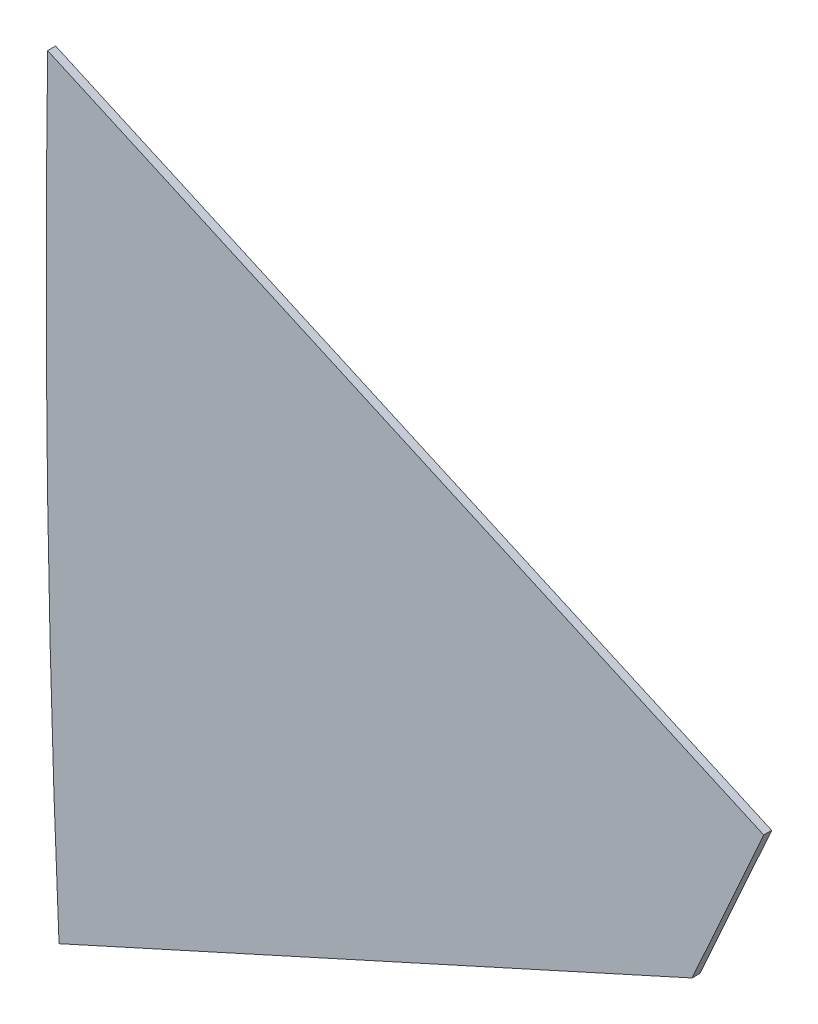
SolidWorks part; units mm, degrees
ref_plane "Plane Left" through (0, 0, 0) normal (0, 0, 1) x (1, 0, 0)
ref_plane "Plane Top" through (0, 0, 0) normal (0, 1, 0) x (1, 0, 0)
ref_plane "Plane Front" through (0, 0, 0) normal (1, 0, 0) x (0, 0, -1)
sketch "Sketch, Layout in Left plane" plane through (0, 0, 0) normal (0, 0, 1) x (1, 0, 0)
  line L0 (0, 0) -> (2438.4, 0) construction
  line L1 (2438.4, 0) -> (3438.525, 5791.2) construction
  line L2 (2438.4, 0) -> (3591.5584, 144.7101) construction
  line L4 (9.525, -304.8) -> (3438.525, 5791.2)
  line L5 (2438.4, 0) -> (2119.6797, -1845.5425) construction
  line L6 (2438.4, 0) -> (1532.9859, -517.7594) construction
  line L7 (1532.9859, -517.7594) -> (3591.5584, 144.7101) construction
  line L8 (1532.9859, -517.7594) -> (2119.6797, -1845.5425) construction
  line L9 (1532.9859, -517.7594) -> (3210.1749, -1270.1567) construction
  line L10 (2438.4, 0) -> (3428.7883, 566.3517) construction
  line L11 (1724.025, 2743.2) -> (1159.8354, 3060.5567)
  line L12 (1724.025, 2743.2) -> (2438.4, 0) construction
  line L13 (2438.4, 0) -> (9.525, -304.8) construction
  line L14 (3210.1749, -1270.1567) -> (2438.4, 0) construction
  line L15 (1985.693, -258.8797) -> (2769.1787, -1628.9737) construction
  line L16 (2119.6797, -1845.5425) -> (3591.5584, 144.7101)
  line L17 (1724.025, 2743.2) -> (771.525, 2743.2) construction
  line L18 (1985.693, -258.8797) -> (2830.8492, -883.9096) construction
  line L19 (2818.8646, -1810.0806) -> (3303.3993, -1154.9) construction
  line L20 (2855.619, -850.4162) -> (3241.0348, -1135.448)
  line L21 (1532.9859, -517.7594) -> (2.9158, 168.6396) construction
  line L22 (59.423, -321.2693) -> (391.6572, -127.5468) construction
  line L24 (1532.9859, -517.7594) -> (542.5977, -1084.111) construction
  line L25 (12.6382, -299.2655) -> (391.6572, -127.5468)
  line L26 (391.6572, -127.5468) -> (434.5423, -31.9505)
  line L27 (434.5423, -31.9505) -> (5.8071, 160.3828)
  line L29 (5.8071, 160.3828) -> (7.7553, 211.1455)
  line L30 (2.6835, 161.7841) -> (4.6317, 212.5467)
  line L31 (588.3016, -156.6053) -> (269.3395, -13.517) construction
  line L33 (381.3693, -119.4518) -> (422.9549, -26.7523)
  line L34 (237.5559, 56.4189) -> (154.3847, -128.9801)
  line L35 (154.3847, -128.9801) -> (165.9722, -134.1783)
  line L36 (165.9722, -134.1783) -> (249.1433, 51.2207)
  line L37 (12.6382, -299.2655) -> (-6.0408, -332.4725)
  line L38 (381.3693, -119.4518) -> (392.9568, -124.65)
  line L39 (59.423, -321.2693) -> (5.8071, 160.3828) construction
  ellipse E1 centre (1985.693, -258.8797) end of major axis (542.5977, -1084.111) minor radius 1578.2926 (542.5977, -1084.111) -> (3428.7883, 566.3517) ccw
  parabola Q0 (9.525, -304.8) -> (3438.525, 5791.2) focus (2438.4, 0) apex (0, 0)
  point P13 (453.548, -33.5168)
  point P45 (59.423, -321.2693)
  point P48 (54.845, -280.1432)
  dimension "D1" = 2438.4
  dimension "D2" = 254
  dimension "D3" = 304.8
  dimension "D4" = 99.798
  dimension "D5" = 6096
  dimension "D6" = 42
  dimension "D7" = 42
  dimension "D8" = 29.763
  dimension "D9" = 53.924
  dimension "D10" = 3.175
  dimension "D11" = 2475.3853
  dimension "D12" = 50.8
  dimension "D13" = 469.9
  dimension "D14" = 104.775
  dimension "D15" = 38.1
  dimension "D16" = 57.15
  dimension "D17" = 12.7
  dimension "D18" = 12.7
  dimension "D19" = 190.5
  dimension "D20" = 203.2
  dimension "D21" = 6.35
  dimension "2c" = 1043.0002
  dimension "D22" = 6.35
  dimension "D23" = 101.6
  dimension "magrad" = 1662.3871
  dimension "D24" = 417.5125
  dimension "D25" = 275.5301
  dimension "D26" = 416.5857
  dimension "D27" = 223.8375
  dimension "D28" = 381.863
  dimension "D29" = 244.8476
ref_plane "Pl-4 Primary face plane" through (1724.025, 2743.2, 0) normal (-0.8716, 0.4903, 0) x (0, 0, 1)
sketch "Sketch1" plane through (0, 0, 0) normal (0, 0, 1) x (1, 0, 0)
  line L0 (0, 0) -> (2438.4, 0) construction
  line L1 (0, 0) -> (2438.4, 0) construction
  parabola Q0 (9.525, -304.8) -> (3438.525, 5791.2) focus (2438.4, 0) apex (0, 0) construction
  parabola Q1 (0, 0) -> (3700.8323, 6008.0311) focus (2438.4, 0) apex (0, 0)
surface "SR-1 Primary, Surface-Revolve1." sketch "Sketch1" parameters "D1"=360
ref_plane "Plane1" through (0, 0, -127) normal (0, 0, 1) x (1, 0, 0)
sketch "Sketch2" plane through (0, 0, -127) normal (0, 0, 1) x (1, 0, 0)
  line L0 (12.6382, -299.2655) -> (391.6572, -127.5468) construction
  line L1 (391.6572, -127.5468) -> (434.5423, -31.9505) construction
  line L2 (434.5423, -31.9505) -> (5.8071, 160.3828) construction
  line L3 (12.6382, -299.2655) -> (391.6572, -127.5468)
  line L4 (391.6572, -127.5468) -> (434.5423, -31.9505)
  line L5 (434.5423, -31.9505) -> (5.8071, 160.3828)
  arc A0 (5.8071, 160.3828) -> (12.6382, -299.2655) centre (7624.9143, 43.7393) ccw
  dimension "D1" = 7620
extrude "Base-Extrude" add sketch "Sketch2" along normal blind 4.7752
